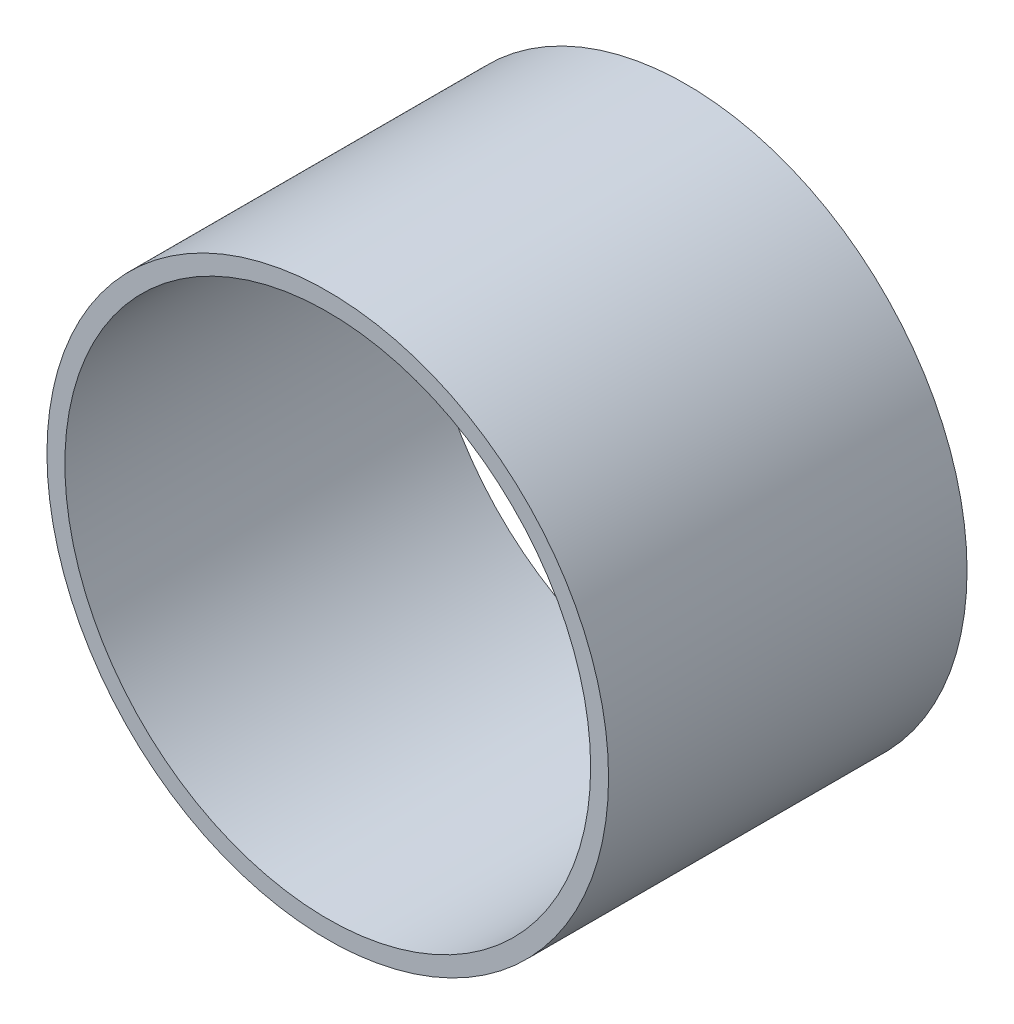
SolidWorks part; units mm, degrees
ref_plane "Front Plane" through (0, 0, 0) normal (0, 0, 1) x (1, 0, 0)
ref_plane "Top Plane" through (0, 0, 0) normal (0, 1, 0) x (1, 0, 0)
ref_plane "Right Plane" through (0, 0, 0) normal (1, 0, 0) x (0, 0, -1)
sketch "Sketch2" plane through (0, 0, 0) normal (0, 0, 1) x (1, 0, 0)
  circle A0 centre (0, 0) radius 596.9
  dimension "D1" = 1193.8
extrude "Boss-Extrude1" add sketch "Sketch2" along normal blind 762
sketch "Sketch3" plane through (0, 0, 762) normal (0, 0, 1) x (1, 0, 0)
  circle A0 centre (0, 0) radius 558.8
  dimension "D1" = 1117.6
extrude "Cut-Extrude1" cut sketch "Sketch3" against normal blind 762
